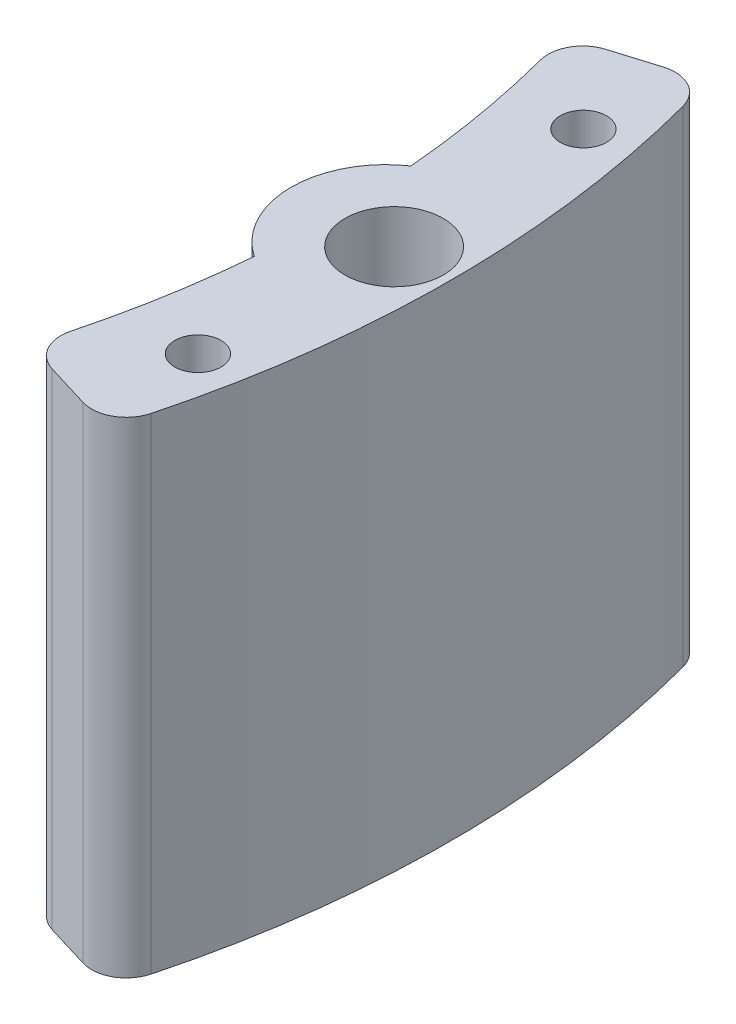
SolidWorks part; units mm, degrees
ref_plane "Front Plane" through (0, 0, 0) normal (0, 0, 1) x (1, 0, 0)
ref_plane "Top Plane" through (0, 0, 0) normal (0, 1, 0) x (1, 0, 0)
ref_plane "Right Plane" through (0, 0, 0) normal (1, 0, 0) x (0, 0, -1)
sketch "Sketch1" plane through (0, 0, 0) normal (0, 1, 0) x (1, 0, 0)
  line L0 (-7.7053, 23.0875) -> (1.8612, 26)
  line L1 (-7.7053, -23.0875) -> (1.8612, -26)
  line L2 (-84.3014, 0) -> (5.6986, 0) construction
  line L3 (1.8612, 26) -> (1.8612, -26) construction
  arc A0 (1.8612, -26) -> (1.8612, 26) centre (-84.3014, 0) ccw
  arc A1 (-7.7053, -23.0875) -> (-7.7053, 23.0875) centre (-84.3014, 0) ccw
  dimension "D1" = 180
  dimension "D2" = 160
  dimension "D3" = 52
extrude "Boss-Extrude1" add sketch "Sketch1" along normal blind 42
fillet "Fillet1" radius 3 4 edges at (1.8612, 21, -26) (-7.7053, 21, -23.0875) (-7.7053, 21, 23.0875) (1.8612, 21, 26)
sketch "Sketch3" plane through (0, 42, 0) normal (0, 1, 0) x (1, 0, 0)
  circle A0 centre (0.7331, 0) radius 4.25
  dimension "D1" = 8.5
extrude "Cut-Extrude1" cut sketch "Sketch3" against normal through all
sketch "Sketch4" plane through (0, 0, 0) normal (0, 1, 0) x (1, 0, 0)
  line L0 (-3.7574, -7.2655) -> (-3.7574, 7.2655)
  arc A0 (-3.7574, 7.2655) -> (-3.7574, -7.2655) centre (0, 0) ccw
extrude "Boss-Extrude2" add sketch "Sketch4" along normal blind 42
sketch "Sketch5" plane through (0, 0, 0) normal (0, -1, 0) x (1, 0, 0)
  line L0 (-4.8949, 23.9431) -> (-1.0656, 25.1089) construction
  line L1 (-1.0656, -25.1089) -> (-4.8949, -23.9431) construction
  arc A0 (-2.9803, 24.526) -> (-2.9803, -24.526) centre (-52.0668, 0) ccw
  arc A1 (-2.9803, 24.526) -> (-2.9803, -24.526) centre (-52.0668, 0) cw
  circle A2 centre (0.1061, -17) radius 2
  circle A3 centre (0.2664, 16.5) radius 2
  dimension "D1" = 4
  dimension "D2" = 4
  dimension "D3" = 17
  dimension "D4" = 16.5
extrude "Cut-Extrude2" cut sketch "Sketch5" against normal through all contours A1 A3 | A1 A3 | A1 A2 | A1 A2
